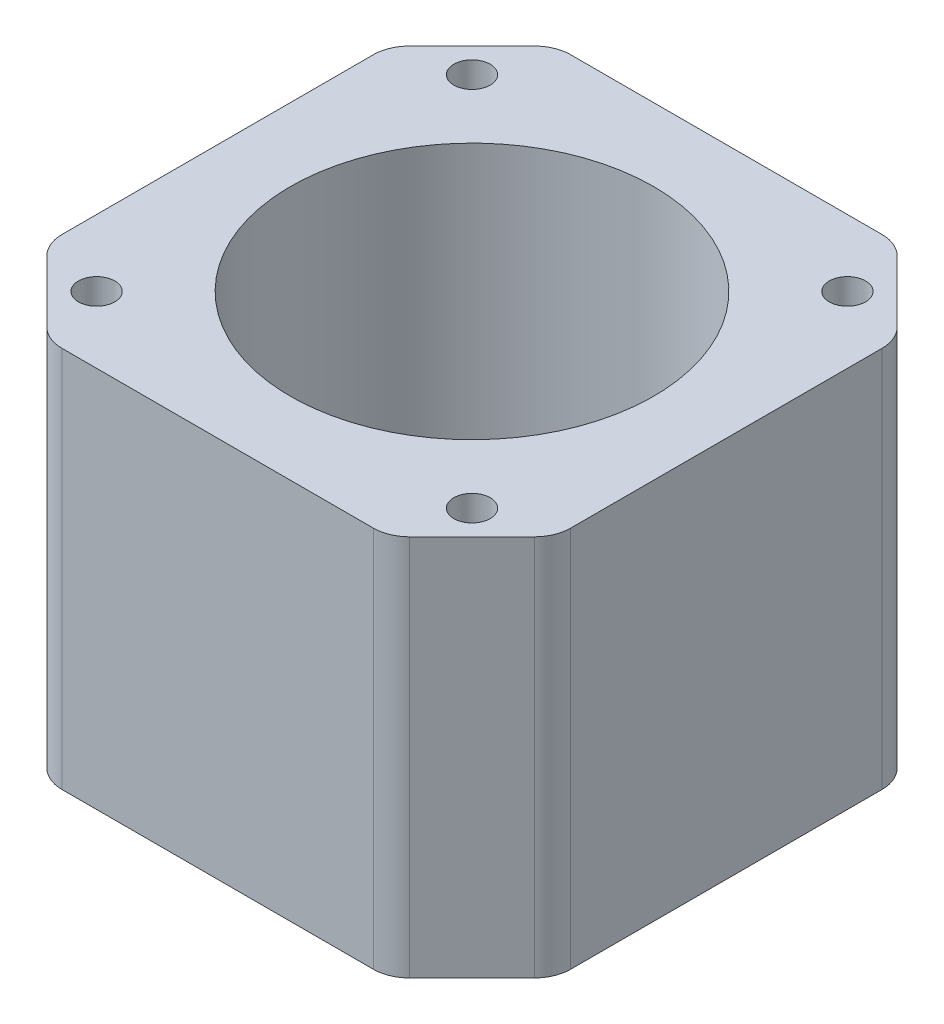
SolidWorks part; units mm, degrees
ref_plane "Alzado" through (0, 0, 0) normal (0, 0, 1) x (1, 0, 0)
ref_plane "Planta" through (0, 0, 0) normal (0, 1, 0) x (1, 0, 0)
ref_plane "Vista lateral" through (0, 0, 0) normal (1, 0, 0) x (0, 0, -1)
ref_plane "Plano4" through (0, 31.55, 0) normal (0, 1, 0) x (1, 0, 0)
sketch "Croquis1" plane through (0, 31.55, 0) normal (0, 1, 0) x (1, 0, 0)
  line L0 (-12.8574, -21) -> (12.8574, -21)
  line L1 (14.9787, -20.1213) -> (20.1213, -14.9787)
  line L2 (21, -12.8574) -> (21, 12.8574)
  line L3 (20.1213, 14.9787) -> (14.9787, 20.1213)
  line L4 (12.8574, 21) -> (-12.8574, 21)
  line L5 (-14.9787, 20.1213) -> (-20.1213, 14.9787)
  line L6 (-21, 12.8574) -> (-21, -12.8574)
  line L7 (-20.1213, -14.9787) -> (-14.9787, -20.1213)
  circle A0 centre (15.5, -15.5) radius 1.5
  circle A1 centre (0, 0) radius 15
  circle A2 centre (15.5, 15.5) radius 1.5
  circle A3 centre (-15.5, -15.5) radius 1.5
  circle A4 centre (-15.5, 15.5) radius 1.5
  arc A5 (12.8574, -21) -> (14.9787, -20.1213) centre (12.8574, -18) ccw
  arc A6 (20.1213, -14.9787) -> (21, -12.8574) centre (18, -12.8574) ccw
  arc A7 (21, 12.8574) -> (20.1213, 14.9787) centre (18, 12.8574) ccw
  arc A8 (14.9787, 20.1213) -> (12.8574, 21) centre (12.8574, 18) ccw
  arc A9 (-12.8574, 21) -> (-14.9787, 20.1213) centre (-12.8574, 18) ccw
  arc A10 (-20.1213, 14.9787) -> (-21, 12.8574) centre (-18, 12.8574) ccw
  arc A11 (-21, -12.8574) -> (-20.1213, -14.9787) centre (-18, -12.8574) ccw
  arc A12 (-14.9787, -20.1213) -> (-12.8574, -21) centre (-12.8574, -18) ccw
extrude "Saliente-Extruir1" add sketch "Croquis1" against normal blind 31.55
